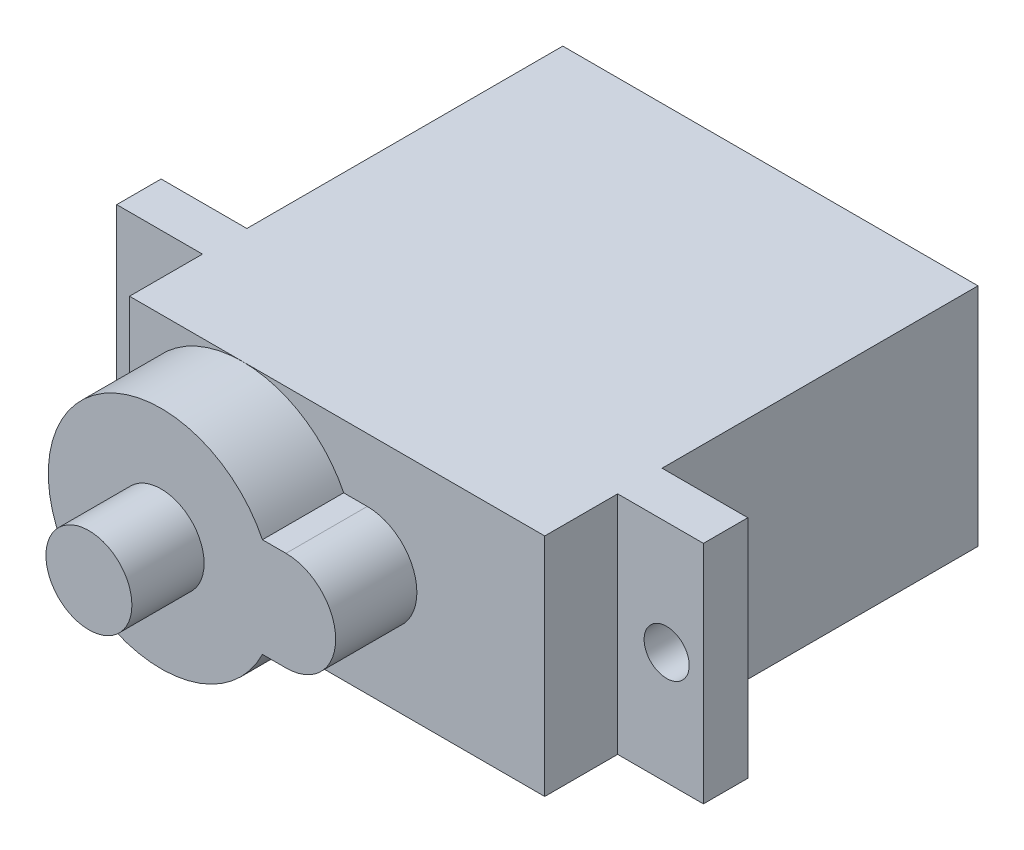
SolidWorks part; units mm, degrees
ref_plane "前视基准面" through (0, 0, 0) normal (0, 0, 1) x (1, 0, 0)
ref_plane "上视基准面" through (0, 0, 0) normal (0, 1, 0) x (1, 0, 0)
ref_plane "右视基准面" through (0, 0, 0) normal (1, 0, 0) x (0, 0, -1)
sketch "草图1" plane through (0, 0, 0) normal (0, 0, 1) x (1, 0, 0)
  line L1 (0, 0) -> (23, 0)
  line L2 (0, 0) -> (0, -12.5)
  line L3 (0, -12.5) -> (23, -12.5)
  line L4 (23, 0) -> (23, -12.5)
  dimension "D1" = 23
  dimension "D2" = 12.5
extrude "凸台-拉伸1" add sketch "草图1" along normal blind 24
ref_plane "基准面1" through (0, 0, 17.5) normal (0, 0, 1) x (1, 0, 0)
sketch "草图2" plane through (0, 0, 17.5) normal (0, 0, 1) x (1, 0, 0)
  line L0 (0, -12.5) -> (23, -12.5) construction
  line L1 (-4.75, 0) -> (27.75, 0)
  line L2 (-4.75, 0) -> (-4.75, -12.5)
  line L3 (-4.75, -12.5) -> (27.75, -12.5)
  line L4 (27.75, 0) -> (27.75, -12.5)
  line L5 (11.5, 0) -> (11.5, -12.5) construction
  line L6 (23, 0) -> (0, 0) construction
  dimension "D1" = 32.5
extrude "凸台-拉伸2" add sketch "草图2" along normal blind 2.46
sketch "草图3" plane through (0, 0, 24) normal (0, 0, 1) x (1, 0, 0)
  line L0 (0, -6.25) -> (23, -6.25) construction
  line L1 (0, 0) -> (0, -12.5) construction
  line L2 (23, -12.5) -> (23, 0) construction
  line L3 (0, 0) -> (0, -12.5) construction
  line L4 (23, 0) -> (0, 0) construction
  line L5 (13.1678, -3.5) -> (11.8625, -3.5)
  line L6 (13.1678, -9) -> (11.8625, -9)
  arc A0 (11.8625, -3.5) -> (11.8625, -9) centre (6.25, -6.25) ccw
  arc A1 (13.1678, -9) -> (13.1678, -3.5) centre (13.1678, -6.25) ccw
  dimension "D1" = 5.5
extrude "凸台-拉伸3" add sketch "草图3" along normal blind 4.5
sketch "草图4" plane through (0, 0, 28.5) normal (0, 0, 1) x (1, 0, 0)
  circle A0 centre (6.25, -6.25) radius 2.3812
extrude "凸台-拉伸4" add sketch "草图4" along normal blind 4
sketch "草图6" plane through (0, 0, 19.96) normal (0, 0, 1) x (1, 0, 0)
  line L0 (-4.75, -6.25) -> (27.75, -6.25) construction
  line L1 (-4.75, 0) -> (-4.75, -12.5) construction
  line L2 (27.75, -12.5) -> (27.75, 0) construction
  line L3 (11.5, 0) -> (11.5, -12.5) construction
  line L4 (23, 0) -> (6.25, 0) construction
  line L5 (6.25, -12.5) -> (23, -12.5) construction
  circle A0 centre (-2.2865, -6.25) radius 1.25
  circle A1 centre (25.7135, -6.25) radius 1.25
  dimension "D1" = 28
  dimension "D2" = 2.5
extrude "切除-拉伸1" cut sketch "草图6" against normal through all
